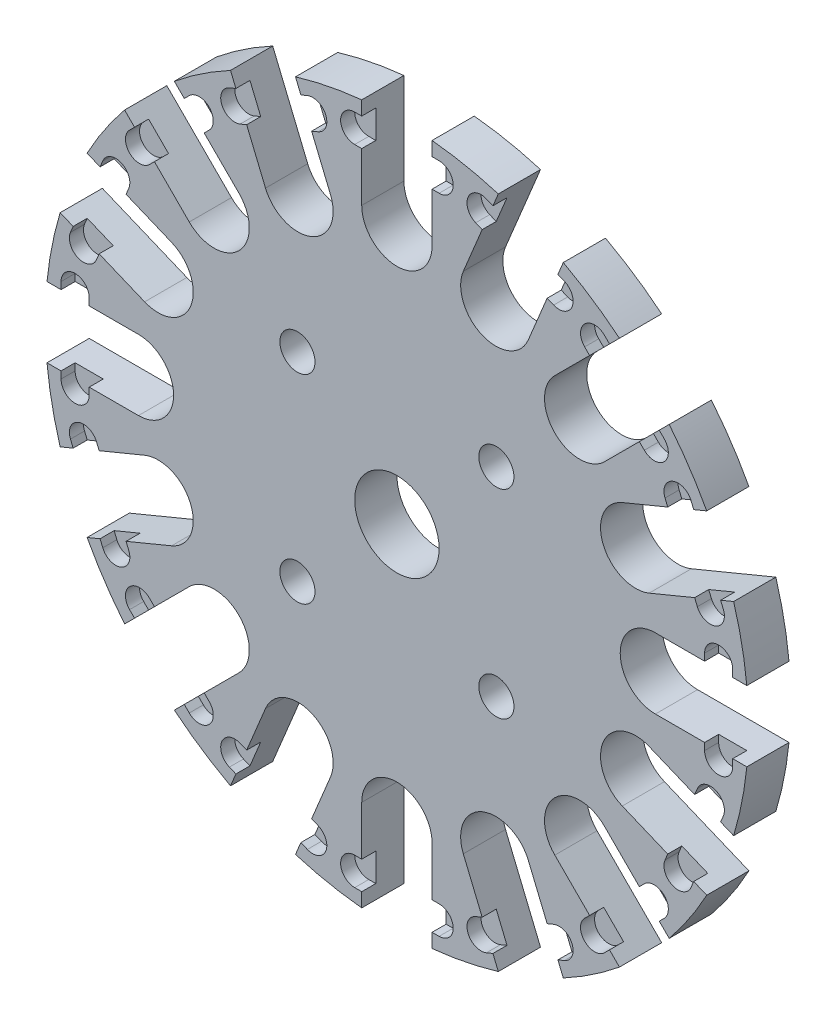
SolidWorks part; units mm, degrees
ref_plane "Plan de face" through (0, 0, 0) normal (0, 0, 1) x (1, 0, 0)
ref_plane "Plan de dessus" through (0, 0, 0) normal (0, 1, 0) x (1, 0, 0)
ref_plane "Plan de droite" through (0, 0, 0) normal (1, 0, 0) x (0, 0, -1)
sketch "Esquisse1" plane through (0, 0, 0) normal (0, 0, 1) x (1, 0, 0)
  circle A0 centre (0, 0) radius 25
  dimension "D1" = 50
extrude "Extrusion1" add sketch "Esquisse1" along normal blind 3
sketch "Esquisse2" plane through (0, 0, 3) normal (0, 0, 1) x (1, 0, 0)
  line L1 (0, 35.6055) -> (0, -30.9749) construction
  line L2 (-2.5, 24.8747) -> (-2.5, 18.3747)
  line L3 (2.5, 24.8747) -> (2.5, 18.3747)
  line L4 (7.2094, 23.9379) -> (4.722, 17.9327)
  line L5 (11.8288, 22.0245) -> (9.3414, 16.0193)
  line L6 (15.8213, 19.3568) -> (11.2251, 14.7606)
  line L7 (19.3568, 15.8213) -> (14.7606, 11.2251)
  line L8 (22.0245, 11.8288) -> (16.0193, 9.3414)
  line L9 (23.9379, 7.2094) -> (17.9327, 4.722)
  line L10 (24.8747, 2.5) -> (18.3747, 2.5)
  line L11 (24.8747, -2.5) -> (18.3747, -2.5)
  line L12 (23.9379, -7.2094) -> (17.9327, -4.722)
  line L13 (22.0245, -11.8288) -> (16.0193, -9.3414)
  line L14 (19.3568, -15.8213) -> (14.7606, -11.2251)
  line L15 (15.8213, -19.3568) -> (11.2251, -14.7606)
  line L16 (11.8288, -22.0245) -> (9.3414, -16.0193)
  line L17 (7.2094, -23.9379) -> (4.722, -17.9327)
  line L18 (2.5, -24.8747) -> (2.5, -18.3747)
  line L19 (-2.5, -24.8747) -> (-2.5, -18.3747)
  line L20 (-7.2094, -23.9379) -> (-4.722, -17.9327)
  line L21 (-11.8288, -22.0245) -> (-9.3414, -16.0193)
  line L22 (-15.8213, -19.3568) -> (-11.2251, -14.7606)
  line L23 (-19.3568, -15.8213) -> (-14.7606, -11.2251)
  line L24 (-22.0245, -11.8288) -> (-16.0193, -9.3414)
  line L25 (-23.9379, -7.2094) -> (-17.9327, -4.722)
  line L26 (-24.8747, -2.5) -> (-18.3747, -2.5)
  line L27 (-24.8747, 2.5) -> (-18.3747, 2.5)
  line L28 (-23.9379, 7.2094) -> (-17.9327, 4.722)
  line L29 (-22.0245, 11.8288) -> (-16.0193, 9.3414)
  line L30 (-19.3568, 15.8213) -> (-14.7606, 11.2251)
  line L31 (-15.8213, 19.3568) -> (-11.2251, 14.7606)
  line L32 (-11.8288, 22.0245) -> (-9.3414, 16.0193)
  line L33 (-7.2094, 23.9379) -> (-4.722, 17.9327)
  circle A0 centre (0, 0) radius 3
  circle A1 centre (0, 0) radius 25 construction
  arc A2 (2.5, 18.3747) -> (-2.5, 18.3747) centre (0, 18.3747) cw
  arc A3 (11.8288, 22.0245) -> (7.2094, 23.9379) centre (0, 0) ccw
  arc A4 (9.3414, 16.0193) -> (4.722, 17.9327) centre (7.0317, 16.976) cw
  arc A5 (19.3568, 15.8213) -> (15.8213, 19.3568) centre (0, 0) ccw
  arc A6 (14.7606, 11.2251) -> (11.2251, 14.7606) centre (12.9929, 12.9929) cw
  arc A7 (23.9379, 7.2094) -> (22.0245, 11.8288) centre (0, 0) ccw
  arc A8 (17.9327, 4.722) -> (16.0193, 9.3414) centre (16.976, 7.0317) cw
  arc A9 (24.8747, -2.5) -> (24.8747, 2.5) centre (0, 0) ccw
  arc A10 (18.3747, -2.5) -> (18.3747, 2.5) centre (18.3747, 0) cw
  arc A11 (22.0245, -11.8288) -> (23.9379, -7.2094) centre (0, 0) ccw
  arc A12 (16.0193, -9.3414) -> (17.9327, -4.722) centre (16.976, -7.0317) cw
  arc A13 (15.8213, -19.3568) -> (19.3568, -15.8213) centre (0, 0) ccw
  arc A14 (11.2251, -14.7606) -> (14.7606, -11.2251) centre (12.9929, -12.9929) cw
  arc A15 (7.2094, -23.9379) -> (11.8288, -22.0245) centre (0, 0) ccw
  arc A16 (4.722, -17.9327) -> (9.3414, -16.0193) centre (7.0317, -16.976) cw
  arc A17 (-2.5, -24.8747) -> (2.5, -24.8747) centre (0, 0) ccw
  arc A18 (-2.5, -18.3747) -> (2.5, -18.3747) centre (0, -18.3747) cw
  arc A19 (-11.8288, -22.0245) -> (-7.2094, -23.9379) centre (0, 0) ccw
  arc A20 (-9.3414, -16.0193) -> (-4.722, -17.9327) centre (-7.0317, -16.976) cw
  arc A21 (-19.3568, -15.8213) -> (-15.8213, -19.3568) centre (0, 0) ccw
  arc A22 (-14.7606, -11.2251) -> (-11.2251, -14.7606) centre (-12.9929, -12.9929) cw
  arc A23 (-23.9379, -7.2094) -> (-22.0245, -11.8288) centre (0, 0) ccw
  arc A24 (-17.9327, -4.722) -> (-16.0193, -9.3414) centre (-16.976, -7.0317) cw
  arc A25 (-24.8747, 2.5) -> (-24.8747, -2.5) centre (0, 0) ccw
  arc A26 (-18.3747, 2.5) -> (-18.3747, -2.5) centre (-18.3747, 0) cw
  arc A27 (-22.0245, 11.8288) -> (-23.9379, 7.2094) centre (0, 0) ccw
  arc A28 (-16.0193, 9.3414) -> (-17.9327, 4.722) centre (-16.976, 7.0317) cw
  arc A29 (-15.8213, 19.3568) -> (-19.3568, 15.8213) centre (0, 0) ccw
  arc A30 (-11.2251, 14.7606) -> (-14.7606, 11.2251) centre (-12.9929, 12.9929) cw
  arc A31 (-7.2094, 23.9379) -> (-11.8288, 22.0245) centre (0, 0) ccw
  arc A32 (-4.722, 17.9327) -> (-9.3414, 16.0193) centre (-7.0317, 16.976) cw
  arc A58 (2.5, 24.8747) -> (-2.5, 24.8747) centre (0, 0) ccw
  dimension "D1" = 6
  dimension "D3" = 5
  dimension "D4" = 6.5
extrude "Extrusion3" cut sketch "Esquisse2" against normal blind 10
hole_wizard "Trou taraudé M3x0.51" positions "Esquisse3D2" profile "Esquisse6" tap size "M3x0.5" standard "Ansi Métrique" end condition through all
sketch3d "Esquisse3D2"
  line L0 (-7.0711, 7.0711, 3) -> (-7.0711, -7.0711, 3) construction
  line L1 (-7.0711, -7.0711, 3) -> (7.0711, -7.0711, 3) construction
  circle A4 centre (0, 0, 3) radius 10
  arc A6 (-19.3568, 15.8213, 3) -> (-22.0245, 11.8288, 3) centre (0, 0, 3) ccw construction
  point P0 (-7.0711, 7.0711, 3)
  point P2 (7.0711, 7.0711, 3)
  point P4 (7.0711, -7.0711, 3)
  point P6 (-7.0711, -7.0711, 3)
  point P26 (0, 0, 13)
  point P38 (0, 0, 28)
  dimension "D1" = 20
sketch "Esquisse6" plane through (-7.0711, 7.0711, 3) normal (1, 0, 0) x (0, -1, 0)
  line L0 (0, 0) -> (0, 3)
  line L1 (0, 3) -> (1.25, 3)
  line L2 (1.25, 3) -> (1.25, 0)
  line L5 (1.25, 0) -> (0, 0)
  line L11 (0, -6.35) -> (0, 107.95) construction
  dimension "Diamètre du trou pour taraudage jusqu'au prochain" = 2.5
  dimension "Profondeur du trou pour taraudage jusqu'au prochain" = 3
cosmetic thread "Filetage de perçage1" parameters "D2"=3
cosmetic thread "Filetage de perçage2" parameters "D2"=3
cosmetic thread "Filetage de perçage3" parameters "D2"=3
cosmetic thread "Filetage de perçage4" parameters "D2"=3
sketch "Esquisse8" plane through (0, 0, 3) normal (0, 0, 1) x (1, 0, 0)
  line L0 (-2.5, 24.8747) -> (-2.5, 18.3747) construction
  line L1 (-2.5, 23.8747) -> (-3, 23.8747)
  line L2 (-2.5, 23.8747) -> (-2.5, 21.8747)
  line L3 (-2.5, 21.8747) -> (-3, 21.8747)
  line L4 (6.8267, 23.014) -> (6.3648, 23.2054)
  line L5 (2.5, 18.3747) -> (2.5, 24.8747) construction
  line L6 (2.5, 23.8747) -> (3, 23.8747)
  line L7 (2.5, 23.8747) -> (2.5, 21.8747)
  line L8 (2.5, 21.8747) -> (3, 21.8747)
  line L9 (6.8267, 23.014) -> (6.0614, 21.1663)
  line L10 (6.0614, 21.1663) -> (5.5994, 21.3576)
  line L11 (11.4461, 21.1006) -> (11.9081, 20.9093)
  line L12 (11.4461, 21.1006) -> (10.6808, 19.2529)
  line L13 (10.6808, 19.2529) -> (11.1427, 19.0615)
  line L14 (15.1142, 18.6497) -> (14.7606, 19.0033)
  line L15 (15.1142, 18.6497) -> (13.7, 17.2355)
  line L16 (13.7, 17.2355) -> (13.3464, 17.5891)
  line L17 (18.6497, 15.1142) -> (19.0033, 14.7606)
  line L18 (18.6497, 15.1142) -> (17.2355, 13.7)
  line L19 (17.2355, 13.7) -> (17.5891, 13.3464)
  line L20 (21.1006, 11.4461) -> (20.9093, 11.9081)
  line L21 (21.1006, 11.4461) -> (19.2529, 10.6808)
  line L22 (19.2529, 10.6808) -> (19.0615, 11.1427)
  line L23 (23.014, 6.8267) -> (23.2054, 6.3648)
  line L24 (23.014, 6.8267) -> (21.1663, 6.0614)
  line L25 (21.1663, 6.0614) -> (21.3576, 5.5994)
  line L26 (23.8747, 2.5) -> (23.8747, 3)
  line L27 (23.8747, 2.5) -> (21.8747, 2.5)
  line L28 (21.8747, 2.5) -> (21.8747, 3)
  line L29 (23.8747, -2.5) -> (23.8747, -3)
  line L30 (23.8747, -2.5) -> (21.8747, -2.5)
  line L31 (21.8747, -2.5) -> (21.8747, -3)
  line L32 (23.014, -6.8267) -> (23.2054, -6.3648)
  line L33 (23.014, -6.8267) -> (21.1663, -6.0614)
  line L34 (21.1663, -6.0614) -> (21.3576, -5.5994)
  line L35 (21.1006, -11.4461) -> (20.9093, -11.9081)
  line L36 (21.1006, -11.4461) -> (19.2529, -10.6808)
  line L37 (19.2529, -10.6808) -> (19.0615, -11.1427)
  line L38 (18.6497, -15.1142) -> (19.0033, -14.7606)
  line L39 (18.6497, -15.1142) -> (17.2355, -13.7)
  line L40 (17.2355, -13.7) -> (17.5891, -13.3464)
  line L41 (15.1142, -18.6497) -> (14.7606, -19.0033)
  line L42 (15.1142, -18.6497) -> (13.7, -17.2355)
  line L43 (13.7, -17.2355) -> (13.3464, -17.5891)
  line L44 (11.4461, -21.1006) -> (11.9081, -20.9093)
  line L45 (11.4461, -21.1006) -> (10.6808, -19.2529)
  line L46 (10.6808, -19.2529) -> (11.1427, -19.0615)
  line L47 (6.8267, -23.014) -> (6.3648, -23.2054)
  line L48 (6.8267, -23.014) -> (6.0614, -21.1663)
  line L49 (6.0614, -21.1663) -> (5.5994, -21.3576)
  line L50 (2.5, -23.8747) -> (3, -23.8747)
  line L51 (2.5, -23.8747) -> (2.5, -21.8747)
  line L52 (2.5, -21.8747) -> (3, -21.8747)
  line L53 (-2.5, -23.8747) -> (-3, -23.8747)
  line L54 (-2.5, -23.8747) -> (-2.5, -21.8747)
  line L55 (-2.5, -21.8747) -> (-3, -21.8747)
  line L56 (-6.8267, -23.014) -> (-6.3648, -23.2054)
  line L57 (-6.8267, -23.014) -> (-6.0614, -21.1663)
  line L58 (-6.0614, -21.1663) -> (-5.5994, -21.3576)
  line L59 (-11.4461, -21.1006) -> (-11.9081, -20.9093)
  line L60 (-11.4461, -21.1006) -> (-10.6808, -19.2529)
  line L61 (-10.6808, -19.2529) -> (-11.1427, -19.0615)
  line L62 (-15.1142, -18.6497) -> (-14.7606, -19.0033)
  line L63 (-15.1142, -18.6497) -> (-13.7, -17.2355)
  line L64 (-13.7, -17.2355) -> (-13.3464, -17.5891)
  line L65 (-18.6497, -15.1142) -> (-19.0033, -14.7606)
  line L66 (-18.6497, -15.1142) -> (-17.2355, -13.7)
  line L67 (-17.2355, -13.7) -> (-17.5891, -13.3464)
  line L68 (-21.1006, -11.4461) -> (-20.9093, -11.9081)
  line L69 (-21.1006, -11.4461) -> (-19.2529, -10.6808)
  line L70 (-19.2529, -10.6808) -> (-19.0615, -11.1427)
  line L71 (-23.014, -6.8267) -> (-23.2054, -6.3648)
  line L72 (-23.014, -6.8267) -> (-21.1663, -6.0614)
  line L73 (-21.1663, -6.0614) -> (-21.3576, -5.5994)
  line L74 (-23.8747, -2.5) -> (-23.8747, -3)
  line L75 (-23.8747, -2.5) -> (-21.8747, -2.5)
  line L76 (-21.8747, -2.5) -> (-21.8747, -3)
  line L77 (-23.8747, 2.5) -> (-23.8747, 3)
  line L78 (-23.8747, 2.5) -> (-21.8747, 2.5)
  line L79 (-21.8747, 2.5) -> (-21.8747, 3)
  line L80 (-23.014, 6.8267) -> (-23.2054, 6.3648)
  line L81 (-23.014, 6.8267) -> (-21.1663, 6.0614)
  line L82 (-21.1663, 6.0614) -> (-21.3576, 5.5994)
  line L83 (-21.1006, 11.4461) -> (-20.9093, 11.9081)
  line L84 (-21.1006, 11.4461) -> (-19.2529, 10.6808)
  line L85 (-19.2529, 10.6808) -> (-19.0615, 11.1427)
  line L86 (-18.6497, 15.1142) -> (-19.0033, 14.7606)
  line L87 (-18.6497, 15.1142) -> (-17.2355, 13.7)
  line L88 (-17.2355, 13.7) -> (-17.5891, 13.3464)
  line L89 (-15.1142, 18.6497) -> (-14.7606, 19.0033)
  line L90 (-15.1142, 18.6497) -> (-13.7, 17.2355)
  line L91 (-13.7, 17.2355) -> (-13.3464, 17.5891)
  line L92 (-11.4461, 21.1006) -> (-11.9081, 20.9093)
  line L93 (-11.4461, 21.1006) -> (-10.6808, 19.2529)
  line L94 (-10.6808, 19.2529) -> (-11.1427, 19.0615)
  line L95 (-6.8267, 23.014) -> (-6.3648, 23.2054)
  line L96 (-6.8267, 23.014) -> (-6.0614, 21.1663)
  line L97 (-6.0614, 21.1663) -> (-5.5994, 21.3576)
  arc A0 (-3, 23.8747) -> (-3, 21.8747) centre (-3, 22.8747) ccw
  arc A1 (3, 21.8747) -> (3, 23.8747) centre (3, 22.8747) ccw
  arc A2 (6.3648, 23.2054) -> (5.5994, 21.3576) centre (5.9821, 22.2815) ccw
  arc A3 (11.1427, 19.0615) -> (11.9081, 20.9093) centre (11.5254, 19.9854) ccw
  arc A4 (14.7606, 19.0033) -> (13.3464, 17.5891) centre (14.0535, 18.2962) ccw
  arc A5 (17.5891, 13.3464) -> (19.0033, 14.7606) centre (18.2962, 14.0535) ccw
  arc A6 (20.9093, 11.9081) -> (19.0615, 11.1427) centre (19.9854, 11.5254) ccw
  arc A7 (21.3576, 5.5994) -> (23.2054, 6.3648) centre (22.2815, 5.9821) ccw
  arc A8 (23.8747, 3) -> (21.8747, 3) centre (22.8747, 3) ccw
  arc A9 (21.8747, -3) -> (23.8747, -3) centre (22.8747, -3) ccw
  arc A10 (23.2054, -6.3648) -> (21.3576, -5.5994) centre (22.2815, -5.9821) ccw
  arc A11 (19.0615, -11.1427) -> (20.9093, -11.9081) centre (19.9854, -11.5254) ccw
  arc A12 (19.0033, -14.7606) -> (17.5891, -13.3464) centre (18.2962, -14.0535) ccw
  arc A13 (13.3464, -17.5891) -> (14.7606, -19.0033) centre (14.0535, -18.2962) ccw
  arc A14 (11.9081, -20.9093) -> (11.1427, -19.0615) centre (11.5254, -19.9854) ccw
  arc A15 (5.5994, -21.3576) -> (6.3648, -23.2054) centre (5.9821, -22.2815) ccw
  arc A16 (3, -23.8747) -> (3, -21.8747) centre (3, -22.8747) ccw
  arc A17 (-3, -21.8747) -> (-3, -23.8747) centre (-3, -22.8747) ccw
  arc A18 (-6.3648, -23.2054) -> (-5.5994, -21.3576) centre (-5.9821, -22.2815) ccw
  arc A19 (-11.1427, -19.0615) -> (-11.9081, -20.9093) centre (-11.5254, -19.9854) ccw
  arc A20 (-14.7606, -19.0033) -> (-13.3464, -17.5891) centre (-14.0535, -18.2962) ccw
  arc A21 (-17.5891, -13.3464) -> (-19.0033, -14.7606) centre (-18.2962, -14.0535) ccw
  arc A22 (-20.9093, -11.9081) -> (-19.0615, -11.1427) centre (-19.9854, -11.5254) ccw
  arc A23 (-21.3576, -5.5994) -> (-23.2054, -6.3648) centre (-22.2815, -5.9821) ccw
  arc A24 (-23.8747, -3) -> (-21.8747, -3) centre (-22.8747, -3) ccw
  arc A25 (-21.8747, 3) -> (-23.8747, 3) centre (-22.8747, 3) ccw
  arc A26 (-23.2054, 6.3648) -> (-21.3576, 5.5994) centre (-22.2815, 5.9821) ccw
  arc A27 (-19.0615, 11.1427) -> (-20.9093, 11.9081) centre (-19.9854, 11.5254) ccw
  arc A28 (-19.0033, 14.7606) -> (-17.5891, 13.3464) centre (-18.2962, 14.0535) ccw
  arc A29 (-13.3464, 17.5891) -> (-14.7606, 19.0033) centre (-14.0535, 18.2962) ccw
  arc A30 (-11.9081, 20.9093) -> (-11.1427, 19.0615) centre (-11.5254, 19.9854) ccw
  arc A31 (-5.5994, 21.3576) -> (-6.3648, 23.2054) centre (-5.9821, 22.2815) ccw
  dimension "D2" = 1
  dimension "D5" = 1
  dimension "D1" = 2
  dimension "D3" = 1
  dimension "D4" = 0.5
  dimension "D6" = 2
  dimension "D7" = 0.5
  dimension "D8" = 1
extrude "Extrusion5" cut sketch "Esquisse8" against normal blind 1
